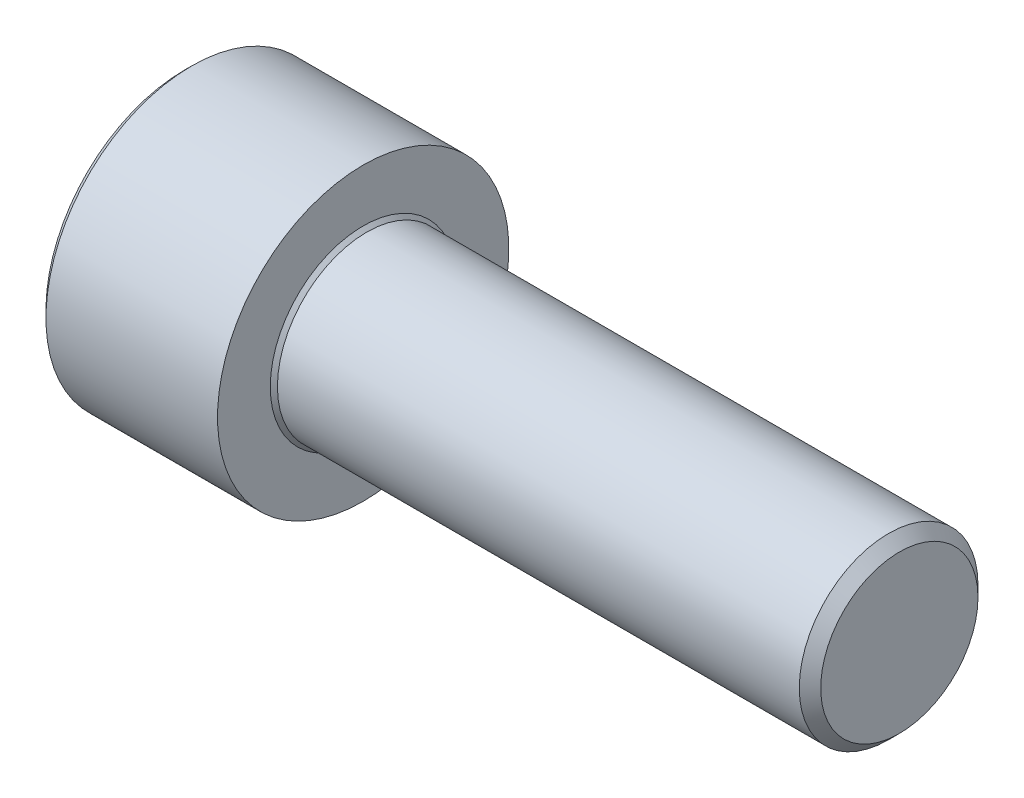
SolidWorks part; units mm, degrees
material "Galvanized Steel"
ref_plane "Front Plane" through (0, 0, 0) normal (0, 0, 1) x (1, 0, 0)
ref_plane "Top Plane" through (0, 0, 0) normal (0, 1, 0) x (1, 0, 0)
ref_plane "Right Plane" through (0, 0, 0) normal (1, 0, 0) x (0, 0, -1)
sketch "Sketch2" plane through (0, 0, 0) normal (1, 0, 0) x (0, 0, -1)
  circle A0 centre (0, 0) radius 5
  dimension "D1" = 10
extrude "Boss-Extrude1" add sketch "Sketch2" against normal blind 30
chamfer "Chamfer1" distance 0.6 angle 45 1 edges at (0, 0, -5)
sketch "Sketch6" plane through (0, 0, 0) normal (0, 0, 1) x (1, 0, 0)
  line L0 (-40, 0) -> (-40, 8.15)
  line L1 (-40, 0) -> (-30, 0)
  line L2 (-40, 8.15) -> (-30, 8.15)
  line L6 (-30, 8.15) -> (-30, 0)
  line L8 (-30, 0) -> (-14.6471, 0) construction
  line L10 (-30, 5) -> (-30, -5) construction
  dimension "D1" = 10
  dimension "D2" = 16.3
revolve "Revolve1" add sketch "Sketch6" angle 360 about L8
sketch "Sketch7" plane through (-40, 0, 0) normal (-1, 0, 0) x (0, 0, 1)
  line L1 (0, 4.6765) -> (-4.05, 2.3383)
  line L2 (-4.05, 2.3383) -> (-4.05, -2.3383)
  line L3 (-4.05, -2.3383) -> (0, -4.6765)
  line L4 (0, -4.6765) -> (4.05, -2.3383)
  line L5 (4.05, -2.3383) -> (4.05, 2.3383)
  line L6 (4.05, 2.3383) -> (0, 4.6765)
  circle A0 centre (0, 0) radius 4.05 construction
  dimension "D1" = 8.1
extrude "Cut-Extrude1" cut sketch "Sketch7" against normal blind 5
sketch "Sketch8" plane through (-40, 0, 0) normal (-1, 0, 0) x (0, 0, 1)
  circle A0 centre (0, 0) radius 4.7265
  dimension "D1" = 0.05
extrude "Cut-Extrude2" cut sketch "Sketch8" against normal blind 1 draft 45
chamfer "Chamfer2" distance 0.4 angle 45 1 edges at (-40, -8.15, 0)
chamfer "Chamfer3" distance 0.2 angle 45 1 edges at (-30, -5, 0)
